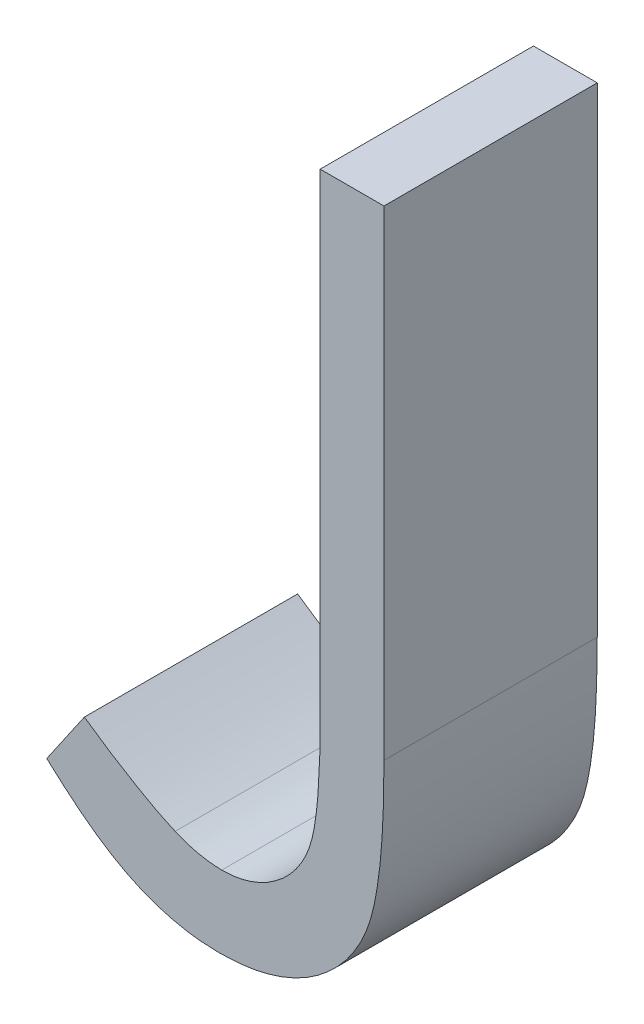
SolidWorks part; units mm, degrees
ref_plane "Plan de face" through (0, 0, 0) normal (0, 0, 1) x (1, 0, 0)
ref_plane "Plan de dessus" through (0, 0, 0) normal (0, 1, 0) x (1, 0, 0)
ref_plane "Plan de droite" through (0, 0, 0) normal (1, 0, 0) x (0, 0, -1)
sketch "Esquisse1" plane through (0, 0, 0) normal (0, 0, 1) x (1, 0, 0)
  text T0 "J" font "Century Gothic" height 5
extrude "Boss.-Extru.1" add sketch "Esquisse1" along normal blind 1.5
